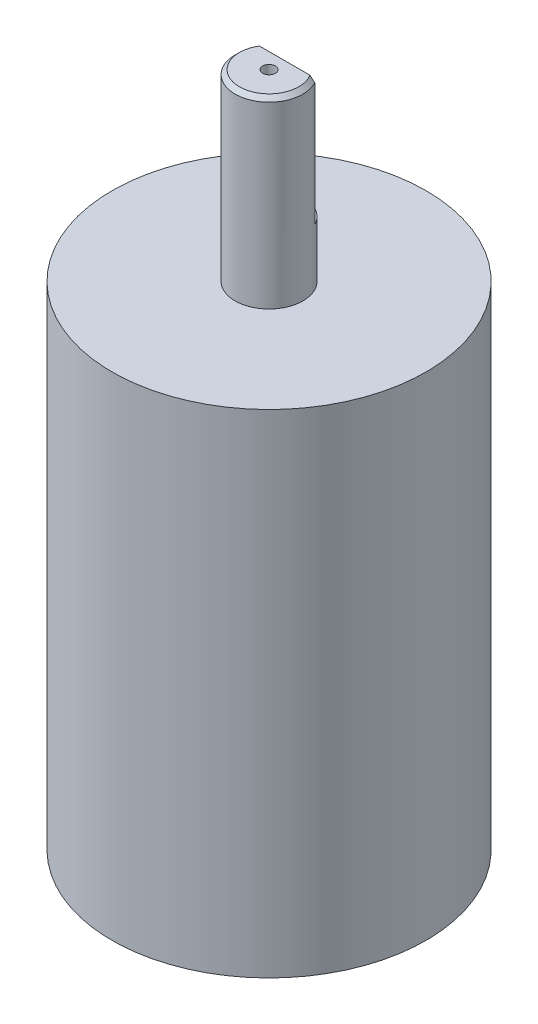
SolidWorks part; units mm, degrees
material "AISI 304"
ref_plane "Front Plane" through (0, 0, 0) normal (0, 0, 1) x (1, 0, 0)
ref_plane "Top Plane" through (0, 0, 0) normal (0, 1, 0) x (1, 0, 0)
ref_plane "Right Plane" through (0, 0, 0) normal (1, 0, 0) x (0, 0, -1)
sketch "Sketch1" plane through (0, 0, 0) normal (1, 0, 0) x (0, 0, -1)
  line L0 (0, -40.8) -> (0, 40.8)
  line L1 (0, 40.8) -> (4, 40.8)
  line L2 (4, 40.8) -> (4, 19.2)
  line L3 (4, 19.2) -> (18.5, 19.2)
  line L4 (18.5, 19.2) -> (18.5, -38.8)
  line L5 (18.5, -38.8) -> (4, -38.8)
  line L6 (4, -38.8) -> (4, -40.8)
  line L7 (4, -40.8) -> (0, -40.8)
  point P4 (0, 0)
  dimension "D1" = 58
  dimension "D2" = 60
  dimension "D3" = 4
  dimension "D4" = 21.6
  dimension "D5" = 18.5
revolve "Revolve1" add sketch "Sketch1" angle 360 about L0
chamfer "Chamfer1" distance 0.5 angle 45 1 edges at (0, 40.8, -4)
sketch "Sketch2" plane through (0, 40.8, 0) normal (0, 1, 0) x (1, 0, 0)
  line L0 (-3.5517, 1.84) -> (3.5517, 1.84)
  circle A0 centre (0, 0) radius 4 construction
  arc A1 (3.5517, 1.84) -> (-3.5517, 1.84) centre (0, 0) ccw
  dimension "D1" = 1.84
extrude "Cut-Extrude1" cut sketch "Sketch2" against normal blind 15
sketch "Sketch3" plane through (0, 40.8, 0) normal (0, 1, 0) x (1, 0, 0)
  circle A0 centre (0, 0) radius 0.75
  dimension "D1" = 1.5
extrude "Cut-Extrude2" cut sketch "Sketch3" against normal through all
